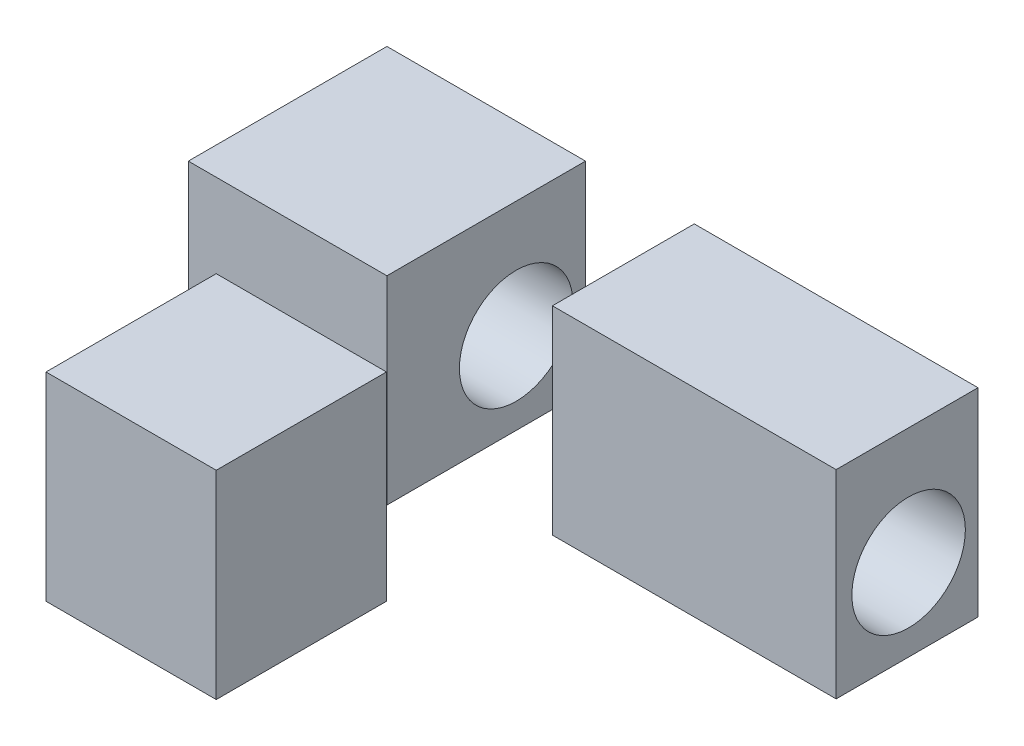
SolidWorks part; units mm, degrees
ref_plane "Front Plane" through (0, 0, 0) normal (0, 0, 1) x (1, 0, 0)
ref_plane "Top Plane" through (0, 0, 0) normal (0, 1, 0) x (1, 0, 0)
ref_plane "Right Plane" through (0, 0, 0) normal (1, 0, 0) x (0, 0, -1)
sketch "Sketch2" plane through (0, 0, 0) normal (0, 1, 0) x (1, 0, 0)
  line L1 (-88.8095, 39.1667) -> (-18.8095, 39.1667)
  line L2 (-88.8095, 39.1667) -> (-88.8095, -30.8333)
  line L3 (-88.8095, -30.8333) -> (-18.8095, -30.8333)
  line L4 (-18.8095, 39.1667) -> (-18.8095, -30.8333)
  line L5 (19.5238, 39.1667) -> (119.5238, 39.1667)
  line L6 (19.5238, 39.1667) -> (19.5238, -10.8333)
  line L7 (19.5238, -10.8333) -> (119.5238, -10.8333)
  line L8 (119.5238, 39.1667) -> (119.5238, -10.8333)
  line L9 (-49.5238, -60.2743) -> (10.4762, -60.2743)
  line L10 (-49.5238, -60.2743) -> (-49.5238, -120.2743)
  line L11 (-49.5238, -120.2743) -> (10.4762, -120.2743)
  line L12 (10.4762, -60.2743) -> (10.4762, -120.2743)
  dimension "D1" = 50
  dimension "D2" = 100
  dimension "D3" = 70
  dimension "D4" = 70
  dimension "D5" = 60
  dimension "D6" = 60
extrude "Boss-Extrude1" add sketch "Sketch2" along normal blind 70
sketch "Sketch3" plane through (119.5238, 0, 0) normal (1, 0, 0) x (0, 0, -1)
  line L0 (-10.8333, 70) -> (-10.8333, 0) construction
  circle A0 centre (14.7144, 28.9023) radius 20
  dimension "D1" = 40
  dimension "D2" = 25.5478
extrude "Cut-Extrude1" cut sketch "Sketch3" against normal through all
